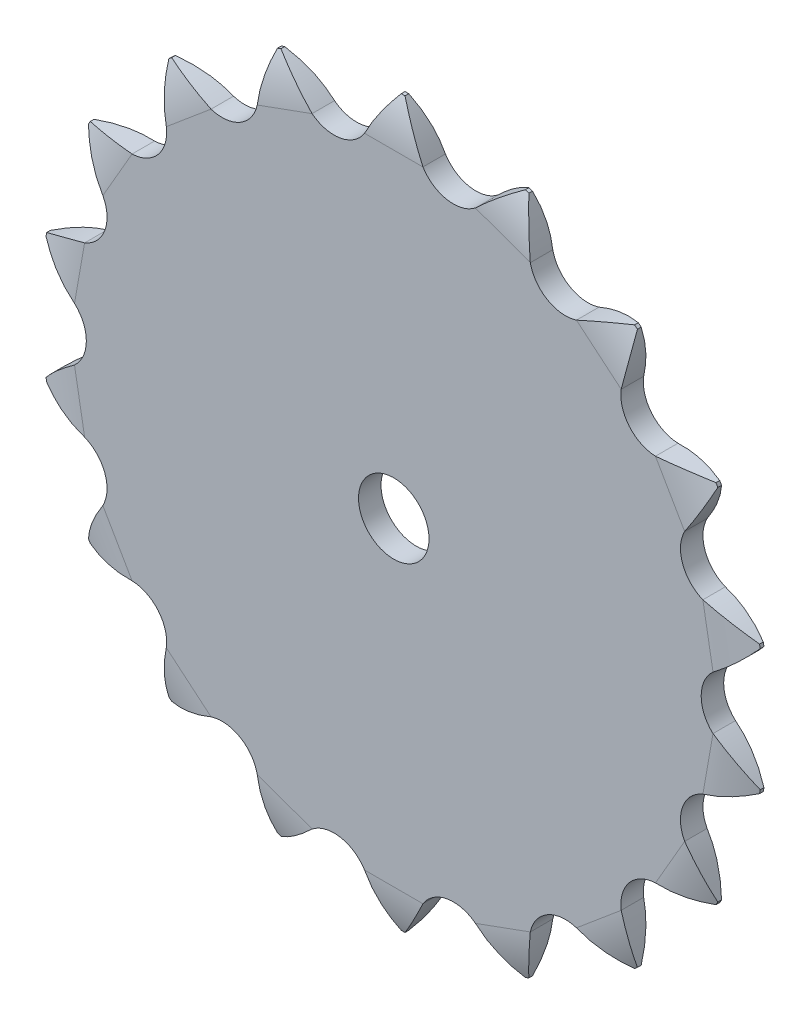
SolidWorks part; units mm, degrees
ref_plane "前视基准面" through (0, 0, 0) normal (0, 0, 1) x (1, 0, 0)
ref_plane "上视基准面" through (0, 0, 0) normal (0, 1, 0) x (1, 0, 0)
ref_plane "右视基准面" through (0, 0, 0) normal (1, 0, 0) x (0, 0, -1)
sketch "草图1" plane through (0, 0, 0) normal (0, 0, 1) x (1, 0, 0)
  line L1 (-22.5, -38.9711) -> (-7.8142, -44.3163)
  line L2 (-7.8142, -44.3163) -> (7.8142, -44.3163)
  line L3 (7.8142, -44.3163) -> (22.5, -38.9711)
  line L4 (22.5, -38.9711) -> (34.472, -28.9254)
  line L5 (34.472, -28.9254) -> (42.2862, -15.3909)
  line L6 (42.2862, -15.3909) -> (45, 0)
  line L7 (45, 0) -> (42.2862, 15.3909)
  line L8 (42.2862, 15.3909) -> (34.472, 28.9254)
  line L9 (34.472, 28.9254) -> (22.5, 38.9711)
  line L10 (22.5, 38.9711) -> (7.8142, 44.3163)
  line L11 (7.8142, 44.3163) -> (-7.8142, 44.3163)
  line L12 (-7.8142, 44.3163) -> (-22.5, 38.9711)
  line L13 (-22.5, 38.9711) -> (-34.472, 28.9254)
  line L14 (-34.472, 28.9254) -> (-42.2862, 15.3909)
  line L15 (-42.2862, 15.3909) -> (-45, 0)
  line L16 (-45, 0) -> (-42.2862, -15.3909)
  line L17 (-42.2862, -15.3909) -> (-34.472, -28.9254)
  line L18 (-34.472, -28.9254) -> (-22.5, -38.9711)
  circle A0 centre (0, 0) radius 44.3163 construction
  circle A1 centre (0, 0) radius 41 construction
  point P22 (0, -44.3163)
sketch "草图3" plane through (0, 0, 0) normal (0, 0, 1) x (1, 0, 0)
  circle A0 centre (-7.8142, 44.3163) radius 4
  circle A1 centre (7.8142, 44.3163) radius 4
  circle A2 centre (-7.8142, 44.3163) radius 1.55
  circle A3 centre (7.8142, 44.3163) radius 1.55
sketch "草图4" plane through (0, 0, 0) normal (0, 0, 1) x (1, 0, 0)
  line L0 (0, 0) -> (-7.8142, 44.3163) construction
  line L1 (-7.8142, 44.3163) -> (-7.8142, 48.3163) construction
  line L2 (-7.8142, 48.3163) -> (7.8142, 48.3163) construction
  line L3 (0, 0) -> (0, 48.3163)
  line L4 (-1.5, 48.3163) -> (-4.6443, 40.7361) construction
  circle A0 centre (-7.8142, 44.3163) radius 4 construction
  circle A1 centre (7.8142, 44.3163) radius 4 construction
  circle A2 centre (0, 0) radius 41 construction
  arc A3 (-0.25, 48.3163) -> (-3.893, 42.5473) centre (24.4902, 28.6587) ccw
  arc A4 (-3.893, 42.5473) -> (-7.1196, 40.3771) centre (-7.9521, 45.0986) cw
  dimension "D3" = 0.25
  dimension "D1" = 1.5
  dimension "D2" = 2.5012
sketch "草图5" plane through (0, 0, 0) normal (0, 0, 1) x (1, 0, 0)
  line L0 (0, 0) -> (0, -10.7057)
  line L1 (-0.25, 48.3163) -> (0.25, 48.3163)
  arc A0 (-7.1196, 40.3771) -> (-3.893, 42.5473) centre (-7.9521, 45.0986) ccw construction
  arc A1 (-0.25, 48.3163) -> (-3.893, 42.5473) centre (24.4902, 28.6587) ccw construction
  arc A2 (-7.1196, 40.3771) -> (-3.893, 42.5473) centre (-7.9521, 45.0986) ccw
  arc A3 (-0.25, 48.3163) -> (-3.893, 42.5473) centre (24.4902, 28.6587) ccw
  arc A4 (7.1196, 40.3771) -> (3.893, 42.5473) centre (7.9521, 45.0986) cw
  arc A5 (0.25, 48.3163) -> (3.893, 42.5473) centre (-24.4902, 28.6587) cw
  circle A6 centre (0, 0) radius 41 construction
  arc A7 (7.1196, 40.3771) -> (-7.1196, 40.3771) centre (0, 0) ccw
extrude "凸台-拉伸1" add sketch "草图5" along normal mid plane 3 contours A7 A4 A5 L1 A3 A2
sketch "草图6" plane through (0, 0, 0) normal (1, 0, 0) x (0, 0, -1)
  line L0 (-1.5, 48.3163) -> (1.5, 48.3163) construction
  line L1 (0, 48.3163) -> (0, 40.3163) construction
  line L2 (1.5, 42.5473) -> (3.3913, 42.5473)
  line L5 (3.3913, 42.5473) -> (3.3913, 49.7229)
  line L6 (3.3913, 49.7229) -> (-3.3913, 49.7229)
  line L7 (-3.3913, 49.7229) -> (-3.3913, 42.5473)
  line L8 (-3.3913, 42.5473) -> (-1.5, 42.5473)
  line L9 (-0.25, 48.3163) -> (0.25, 48.3163)
  arc A0 (-1.5, 42.5473) -> (-0.25, 48.3163) centre (14.0396, 42.2002) cw
  arc A1 (1.5, 42.5473) -> (0.25, 48.3163) centre (-14.0396, 42.2002) ccw
  dimension "D1" = 0.25
extrude "切除-拉伸1" cut sketch "草图6" against normal mid plane 50
pattern_circular "阵列(圆周)1" count 18 over 360 about axis through (0, 0, 0) along (0, 0, 1) of bodies 107
sketch "草图7" plane through (0, 0, 0) normal (0, 0, 1) x (1, 0, 0)
  circle A0 centre (0, 0) radius 41 construction
  circle A1 centre (0, 0) radius 41
  circle A2 centre (0, 0) radius 41
  circle A3 centre (0, 0) radius 4.7
extrude "凸台-拉伸2" add sketch "草图7" along normal mid plane 3 contours A1 A3
